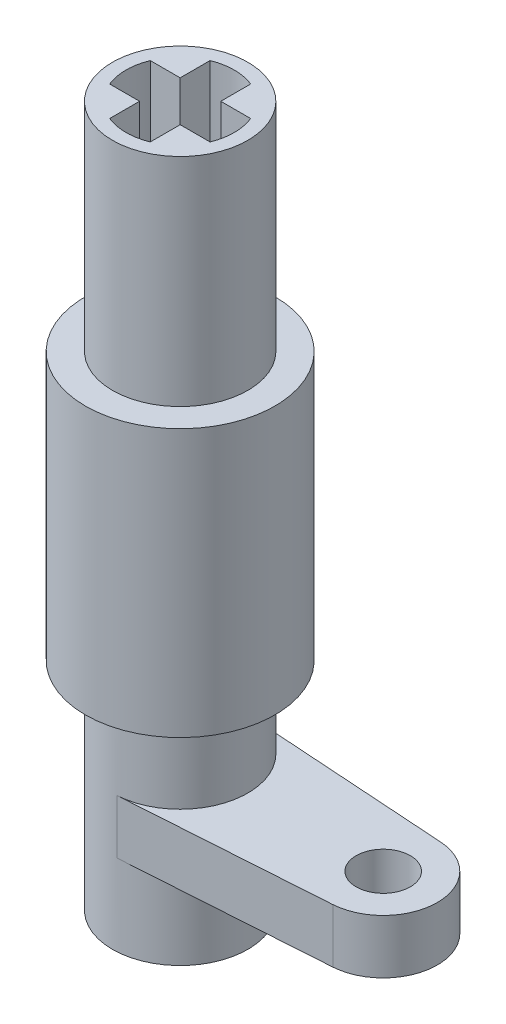
SolidWorks part; units mm, degrees
ref_plane "前视基准面" through (0, 0, 0) normal (0, 0, 1) x (1, 0, 0)
ref_plane "上视基准面" through (0, 0, 0) normal (0, 1, 0) x (1, 0, 0)
ref_plane "右视基准面" through (0, 0, 0) normal (1, 0, 0) x (0, 0, -1)
other "Configuration Table"
sketch "草图1" plane through (0, 0, 0) normal (0, 1, 0) x (1, 0, 0)
  circle A0 centre (0, 0) radius 2.5
  dimension "D1" = 5
extrude "凸台-拉伸1" add sketch "草图1" along normal blind 25.88
sketch "草图2" plane through (0, 0, 0) normal (0, 1, 0) x (1, 0, 0)
  line L0 (-1000, 0) -> (49000, 0) construction
  line L1 (0.1667, 2.4944) -> (7.6333, 1.9956)
  line L2 (0.1667, -2.4944) -> (7.6333, -1.9956)
  circle A0 centre (0, 0) radius 2.5 construction
  arc A1 (0.1667, 2.4944) -> (0.1667, -2.4944) centre (0, 0) ccw
  arc A2 (7.6333, -1.9956) -> (7.6333, 1.9956) centre (7.5, 0) ccw
  circle A3 centre (7.5, 0) radius 1
  dimension "D1" = 4
  dimension "D3" = 2
  dimension "D2" = 7.5
extrude "凸台-拉伸2" add sketch "草图2" along normal blind 2 from offset 3
sketch "草图3" plane through (0, 0, 0) normal (0, 1, 0) x (1, 0, 0)
  line L0 (-1000, 0) -> (49000, 0) construction
  line L1 (0, -1000) -> (0, 49000) construction
  line L4 (-1.854, -0.75) -> (-0.75, -0.75)
  line L6 (1.854, 0.75) -> (0.75, 0.75)
  line L7 (-0.75, 1.854) -> (-0.75, 0.75)
  line L9 (0.75, -1.854) -> (0.75, -0.75)
  line L10 (0.75, -0.75) -> (1.854, -0.75)
  line L11 (-0.75, -0.75) -> (-0.75, -1.854)
  line L12 (0.75, 0.75) -> (0.75, 1.854)
  line L13 (-0.75, 0.75) -> (-1.854, 0.75)
  arc A0 (-1.854, 0.75) -> (-1.854, -0.75) centre (0, 0) ccw
  arc A1 (0.75, 1.854) -> (-0.75, 1.854) centre (0, 0) ccw
  arc A2 (1.854, -0.75) -> (1.854, 0.75) centre (0, 0) ccw
  arc A3 (-0.75, -1.854) -> (0.75, -1.854) centre (0, 0) ccw
  point P10 (0, 1.854)
  point P13 (-1.854, 0)
  dimension "D1" = 4
  dimension "D2" = 1.5
  dimension "D3" = 1.5
  dimension "D4" = 1.104
  dimension "D5" = 2.1213
extrude "切除-拉伸1" cut sketch "草图3" along normal blind 4 contours L10 A2 L6 L12 A1 L7 L13 A0 L4 L11 L9
sketch "草图5" plane through (0, 0, 0) normal (0, 1, 0) x (1, 0, 0)
  line L0 (1.854, 0.75) -> (0.75, 0.75) construction
  line L1 (0.75, 0.75) -> (0.75, 1.854) construction
  line L2 (-0.75, 1.854) -> (-0.75, 0.75) construction
  line L3 (-0.75, 0.75) -> (-1.854, 0.75) construction
  line L4 (-0.75, -0.75) -> (-0.75, -1.854) construction
  line L5 (0.75, -1.854) -> (0.75, -0.75) construction
  line L6 (-1.854, -0.75) -> (-0.75, -0.75) construction
  line L7 (0.75, -0.75) -> (1.854, -0.75) construction
  line L8 (1.854, 0.75) -> (0.75, 0.75)
  line L9 (0.75, 0.75) -> (0.75, 1.854)
  line L10 (-0.75, 1.854) -> (-0.75, 0.75)
  line L11 (-0.75, 0.75) -> (-1.854, 0.75)
  line L12 (-0.75, -0.75) -> (-0.75, -1.854)
  line L13 (0.75, -1.854) -> (0.75, -0.75)
  line L14 (-1.854, -0.75) -> (-0.75, -0.75)
  line L15 (0.75, -0.75) -> (1.854, -0.75)
  arc A0 (0.75, 1.854) -> (-0.75, 1.854) centre (0, 0) ccw construction
  arc A1 (-1.854, 0.75) -> (-1.854, -0.75) centre (0, 0) ccw construction
  arc A2 (-0.75, -1.854) -> (0.75, -1.854) centre (0, 0) ccw construction
  arc A3 (1.854, -0.75) -> (1.854, 0.75) centre (0, 0) ccw construction
  arc A4 (0.75, 1.854) -> (-0.75, 1.854) centre (0, 0) ccw
  arc A5 (-1.854, 0.75) -> (-1.854, -0.75) centre (0, 0) ccw
  arc A6 (-0.75, -1.854) -> (0.75, -1.854) centre (0, 0) ccw
  arc A7 (1.854, -0.75) -> (1.854, 0.75) centre (0, 0) ccw
extrude "切除-拉伸2" cut sketch "草图5" against normal blind 4 from surface at 25.88 starting at face at (0, 25.88, 2.5)
sketch "草图6" plane through (0, 0, 0) normal (0, 1, 0) x (1, 0, 0)
  line L0 (0, 0) -> (0.75, 0) construction
  circle A0 centre (0.75, 0) radius 0.25
  dimension "D2" = 0.5
  dimension "D1" = 0.75
extrude "切除-拉伸3" cut sketch "草图6" against normal blind 0.25 from surface at 21.88 starting at face at (0, 21.88, 0)
sketch "草图7" plane through (0, 0, 0) normal (0, 1, 0) x (1, 0, 0)
  circle A0 centre (0.75, 0) radius 0.25 construction
  circle A1 centre (0.75, 0) radius 0.25
extrude "切除-拉伸4" cut sketch "草图7" along normal blind 0.25 from surface at 4 starting at face at (0, 4, 0)
sketch "草图17" plane through (0, 0, 0) normal (0, 1, 0) x (1, 0, 0)
  circle A0 centre (0, 0) radius 3.5
  dimension "D1" = 7
extrude "凸台-拉伸5" add sketch "草图17" along normal blind 9.88 from offset 8
sketch "草图18" plane through (0, 0, 0) normal (0, 1, 0) x (1, 0, 0)
  circle A0 centre (0, 0) radius 1
  dimension "D1" = 2
extrude "切除-拉伸11" cut sketch "草图18" along normal blind 10
sketch "草图19" plane through (0, 0, 0) normal (0, 1, 0) x (1, 0, 0)
  circle A0 centre (0, 0) radius 1
  dimension "D1" = 2
extrude "切除-拉伸12" cut sketch "草图19" against normal blind 10 from surface at 25.88 starting at face at (0, 25.88, 2.5)
sketch "草图20" plane through (0, 0, 0) normal (0, 0, 1) x (1, 0, 0)
  line L0 (0, -1000) -> (0, 49000) construction
  line L1 (-2, 14.88) -> (2, 14.88)
  line L2 (2, 14.88) -> (2, 16.48)
  line L3 (2, 16.48) -> (-2, 16.48)
  line L4 (-2, 16.48) -> (-2, 14.88)
  line L5 (0.75, 21.88) -> (-0.75, 21.88) construction
  line L6 (-2, 11) -> (2, 11)
  line L7 (2, 11) -> (2, 9.4)
  line L8 (2, 9.4) -> (-2, 9.4)
  line L9 (-2, 9.4) -> (-2, 11)
  line L10 (-1, 4) -> (1, 4) construction
  point P6 (0, 14.88)
  point P13 (0, 11)
  dimension "D1" = 4
  dimension "D2" = 1.6
  dimension "D3" = 7
  dimension "D4" = 1.6
  dimension "D5" = 4
  dimension "D6" = 5.4
sketch "草图22" plane through (0, 0, 0) normal (1, 0, 0) x (0, 0, -1)
  line L1 (-2, 15.88) -> (2, 15.88)
  line L2 (-2, 15.88) -> (-2, 13.88)
  line L3 (-2, 13.88) -> (2, 13.88)
  line L4 (2, 15.88) -> (2, 13.88)
  line L5 (-2, 12) -> (2, 12)
  line L6 (-2, 12) -> (-2, 10)
  line L7 (-2, 10) -> (2, 10)
  line L8 (2, 12) -> (2, 10)
  line L12 (0, 25.88) -> (0, 17.88) construction
  line L13 (3.5, 17.88) -> (-3.5, 17.88) construction
  line L14 (-2.5, 8) -> (2.5, 8) construction
  point P8 (0, 12)
  dimension "D1" = 4
  dimension "D2" = 4
  dimension "D3" = 2
  dimension "D4" = 2
  dimension "D5" = 2
  dimension "D6" = 2
extrude "切除-拉伸13" cut sketch "草图22" against normal blind 10
sketch "草图23" plane through (0, 0, 0) normal (0, 1, 0) x (1, 0, 0)
  line L1 (-2.3094, 0) -> (-1.1547, -2)
  line L2 (-1.1547, -2) -> (1.1547, -2)
  line L3 (1.1547, -2) -> (2.3094, 0)
  line L4 (2.3094, 0) -> (1.1547, 2)
  line L5 (1.1547, 2) -> (-1.1547, 2)
  line L6 (-1.1547, 2) -> (-2.3094, 0)
  circle A0 centre (0, 0) radius 2 construction
  dimension "D1" = 4
extrude "切除-拉伸14" cut sketch "草图23" against normal up to surface (2 mm away) from surface at 15.88 up to face at (-1.5931, 13.88, 0) starting at face at (-1.2287, 15.88, 0)
sketch "草图24" plane through (0, 0, 0) normal (0, 1, 0) x (1, 0, 0)
  line L6 (-2.3094, 0) -> (-1.1547, -2)
  line L7 (-1.1547, -2) -> (1.1547, -2)
  line L8 (1.1547, -2) -> (2.3094, 0)
  line L9 (2.3094, 0) -> (1.1547, 2)
  line L10 (1.1547, 2) -> (-1.1547, 2)
  line L11 (-1.1547, 2) -> (-2.3094, 0)
  line L12 (-2.3094, 0) -> (-1.1547, -2)
  line L13 (-1.1547, -2) -> (1.1547, -2)
  line L14 (1.1547, -2) -> (2.3094, 0)
  line L15 (2.3094, 0) -> (1.1547, 2)
  line L16 (1.1547, 2) -> (-1.1547, 2)
  line L17 (-1.1547, 2) -> (-2.3094, 0)
  dimension "D1" = 0
extrude "切除-拉伸15" cut sketch "草图24" against normal up to surface (2 mm away) from surface at 12 up to face at (-1.2287, 10, 0) starting at face at (-1.5931, 12, 0)
sketch "草图25" plane through (0, 0, 0) normal (0, 1, 0) x (1, 0, 0)
  circle A0 centre (0, 0) radius 1 construction
  circle A1 centre (0, 0) radius 1
extrude "切除-拉伸16" cut sketch "草图25" along normal through all
